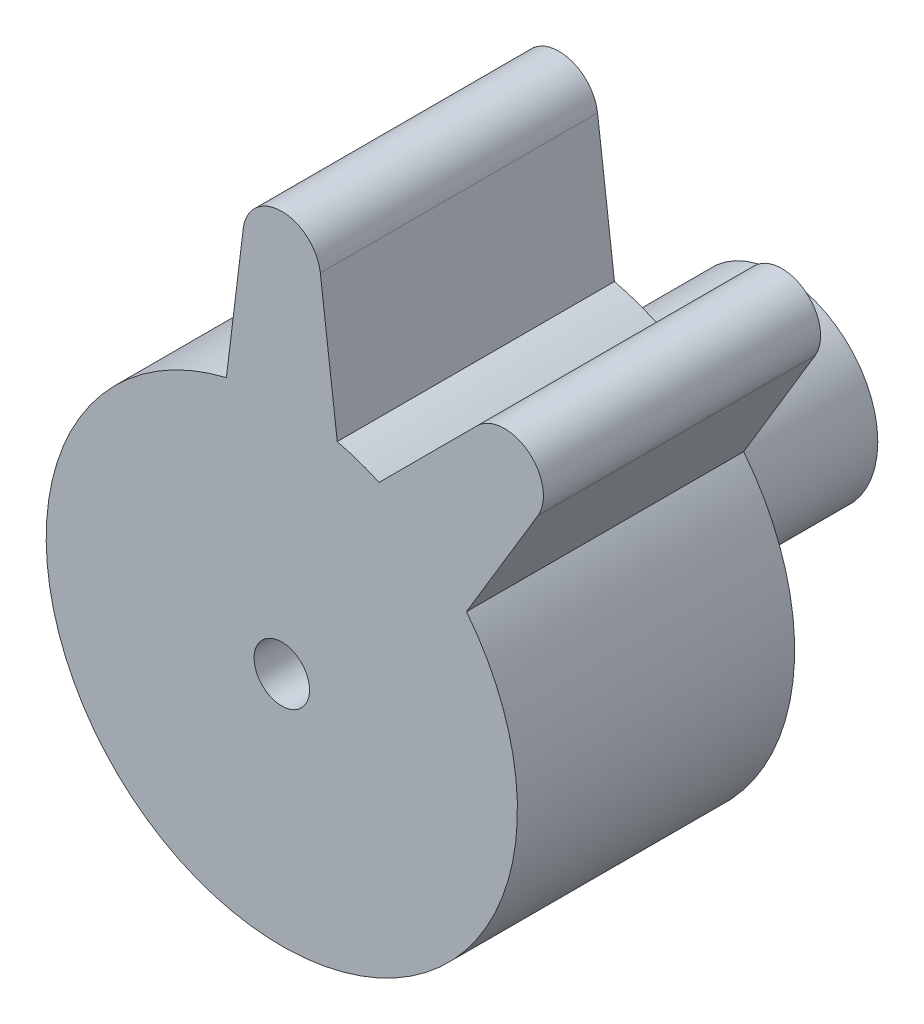
SolidWorks part; units mm, degrees
ref_plane "Front Plane" through (0, 0, 0) normal (0, 0, 1) x (1, 0, 0)
ref_plane "Top Plane" through (0, 0, 0) normal (0, 1, 0) x (1, 0, 0)
ref_plane "Right Plane" through (0, 0, 0) normal (1, 0, 0) x (0, 0, -1)
sketch "Sketch1" plane through (0, 0, 0) normal (0, 0, 1) x (1, 0, 0)
  line L0 (0, 0) -> (0, 51.188) construction
  line L1 (-2, 8.2614) -> (-1.3907, 13.2241)
  line L2 (2, 8.2614) -> (1.3907, 13.2241)
  line L3 (0, 0) -> (22.4184, 65.1077) construction
  line L4 (6.6622, 5.2787) -> (9.2374, 9.5646)
  line L5 (0, 0) -> (31.5145, 40.3367) construction
  line L6 (3.5102, 7.7414) -> (7.0457, 11.2769)
  circle A0 centre (0, 0) radius 8.5
  circle A1 centre (0, 0) radius 1
  arc A2 (-1.3907, 13.2241) -> (1.3907, 13.2241) centre (0, 13.0533) cw
  arc A3 (9.2374, 9.5646) -> (7.0457, 11.2769) centre (8.0364, 10.2862) ccw
  circle A4 centre (0, 0) radius 12 construction
  dimension "D1" = 24
  dimension "D2" = 17
  dimension "D3" = 2
  dimension "D4" = 7
  dimension "D7" = 5
  dimension "D5" = 4
  dimension "D6" = 19
extrude "Boss-Extrude1" add sketch "Sketch1" along normal blind 10
sketch "Sketch5" plane through (0, 0, 0) normal (0, 0, -1) x (-1, 0, 0)
  circle A0 centre (0, 0) radius 2
  circle A1 centre (0, 0) radius 3.5
  dimension "D1" = 7
  dimension "D2" = 4
extrude "Boss-Extrude3" add sketch "Sketch5" along normal blind 8
sketch "Sketch6" plane through (0, 0, 0) normal (1, 0, 0) x (0, 0, -1)
  circle A0 centre (2.5, 0) radius 1
  point P2 (0, 0)
  dimension "D1" = 2
  dimension "D2" = 2.5
extrude "Cut-Extrude1" cut sketch "Sketch6" against normal through all both and the other way through all
